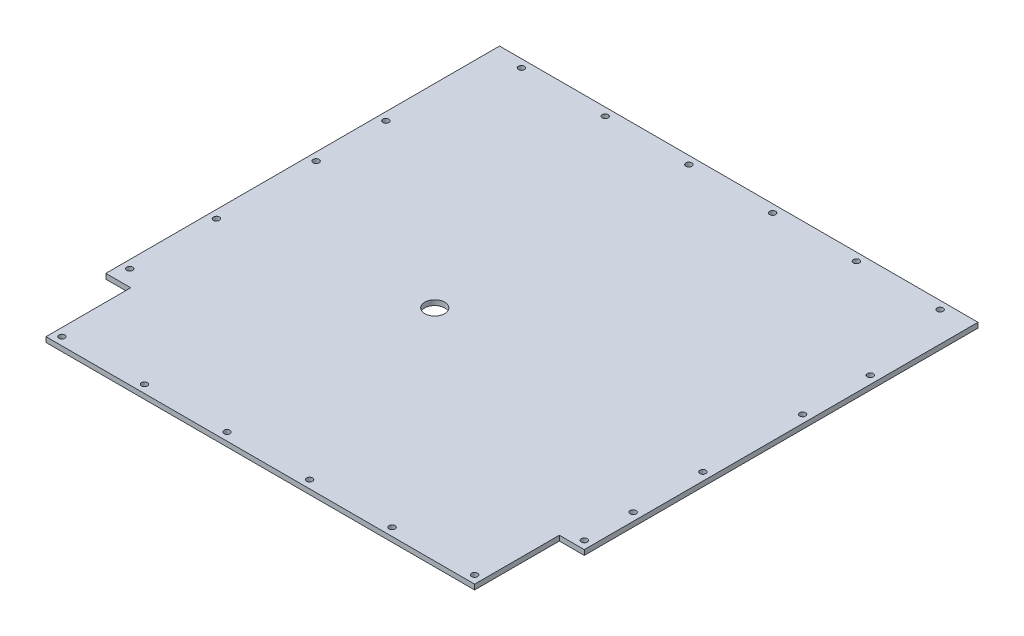
SolidWorks part; units mm, degrees
ref_plane "Front" through (0, 0, 0) normal (0, 0, 1) x (1, 0, 0)
ref_plane "Top" through (0, 0, 0) normal (0, 1, 0) x (1, 0, 0)
ref_plane "Right" through (0, 0, 0) normal (1, 0, 0) x (0, 0, -1)
sketch "Sketch1" plane through (0, 0, 0) normal (0, 1, 0) x (1, 0, 0)
  line L0 (0, 0) -> (0, -50000) construction
  line L1 (-120, -120) -> (-107.5, -120)
  line L2 (-120, -120) -> (-120, -77.5)
  line L3 (-120, -77.5) -> (-107.5, -77.5)
  line L4 (-107.5, -120) -> (-107.5, -77.5)
  line L5 (-120, 120) -> (120, 120)
  line L6 (-120, 120) -> (-120, -120)
  line L7 (-120, -120) -> (120, -120)
  line L8 (120, 120) -> (120, -120)
  line L9 (120, -77.5) -> (107.5, -77.5)
  line L10 (107.5, -120) -> (107.5, -77.5)
  line L11 (-120, 116) -> (120, 116) construction
  line L12 (-116, 120) -> (-116, -77.5) construction
  line L13 (-107.5, -116) -> (107.5, -116) construction
  line L14 (116, -77.5) -> (116, 120) construction
  circle A0 centre (-22.5, -10) radius 5
  point P18 (-105, 116)
  point P19 (-63, 116)
  point P20 (-21, 116)
  point P21 (21, 116)
  point P22 (63, 116)
  point P23 (105, 116)
  point P26 (-116, 59)
  point P27 (-116, 24)
  point P28 (-116, -26)
  point P29 (-116, -69.5)
  point P32 (-103.5, -116)
  point P33 (-20.7, -116)
  point P34 (-62.1, -116)
  point P35 (20.7, -116)
  point P36 (62.1, -116)
  point P37 (103.5, -116)
  point P40 (116, 70)
  point P41 (116, 36)
  point P42 (116, -49)
  point P43 (116, -14)
  point P44 (116, -73.5)
  dimension "D7" = 10
  dimension "D1" = 240
  dimension "D2" = 240
  dimension "D3" = 120
  dimension "D4" = 120
  dimension "D5" = 12.5
  dimension "D6" = 197.5
  dimension "D8" = 130
  dimension "D9" = 97.5
  dimension "D10" = 4
  dimension "D11" = 15
  dimension "D12" = 57
  dimension "D13" = 99
  dimension "D14" = 141
  dimension "D15" = 183
  dimension "D16" = 225
  dimension "D17" = 4
  dimension "D18" = 61
  dimension "D19" = 96
  dimension "D20" = 146
  dimension "D21" = 189.5
  dimension "D22" = 4
  dimension "D23" = 16.5
  dimension "D24" = 57.9
  dimension "D25" = 99.3
  dimension "D26" = 140.7
  dimension "D27" = 182.1
  dimension "D28" = 223.5
  dimension "D29" = 4
  dimension "D30" = 50
  dimension "D31" = 84
  dimension "D32" = 134
  dimension "D33" = 169
  dimension "D34" = 193.5
extrude "Boss-Extrude1" add sketch "Sketch1" along normal blind 2.54 contours L7 L10 L9 L8 L5 L6 L3 L4 A0
sketch "Sketch5" plane through (0, 0, 0) normal (0, -1, 0) x (1, 0, 0)
  point P0 (-103.5, 116)
  point P1 (-62.1, 116)
  point P3 (-20.7, 116)
  point P5 (20.7, 116)
  point P7 (62.1, 116)
  point P9 (103.5, 116)
  point P11 (116, 73.5)
  point P13 (116, 49)
  point P15 (116, 14)
  point P17 (116, -36)
  point P19 (116, -70)
  point P21 (105, -116)
  point P23 (63, -116)
  point P25 (21, -116)
  point P27 (-21, -116)
  point P29 (-63, -116)
  point P31 (-105, -116)
  point P33 (-116, -59)
  point P35 (-116, -24)
  point P37 (-116, 26)
  point P39 (-116, 69.5)
hole_wizard "Ø3.0 (3) Diameter Hole1" positions "Sketch9" profile "Sketch8" hole size "Ø3.0" standard "AS" end condition up to next
sketch "Sketch9" plane through (0, 0, 0) normal (0, 1, 0) x (1, 0, 0)
  point P0 (-103.5, -116)
  point P3 (-62.1, -116)
  point P6 (-20.7, -116)
  point P9 (20.7, -116)
  point P12 (62.1, -116)
  point P15 (103.5, -116)
  point P18 (116, -73.5)
  point P21 (116, -49)
  point P24 (116, -14)
  point P27 (116, 36)
  point P30 (116, 70)
  point P33 (105, 116)
  point P36 (63, 116)
  point P39 (21, 116)
  point P42 (-21, 116)
  point P45 (-63, 116)
  point P48 (-105, 116)
  point P51 (-116, 59)
  point P54 (-116, 24)
  point P57 (-116, -26)
  point P60 (-116, -69.5)
sketch "Sketch8" plane through (-103.5, 0, 116) normal (1, 0, 0) x (0, 0, -1)
  line L0 (0, 0) -> (0, 2.54)
  line L1 (0, 2.54) -> (1.5, 2.54)
  line L2 (1.5, 2.54) -> (1.5, 0)
  line L5 (1.5, 0) -> (0, 0)
  line L11 (0, -6.35) -> (0, 107.95) construction
  dimension "Thru Hole Dia." = 3
  dimension "Thru Hole Depth" = 2.54
